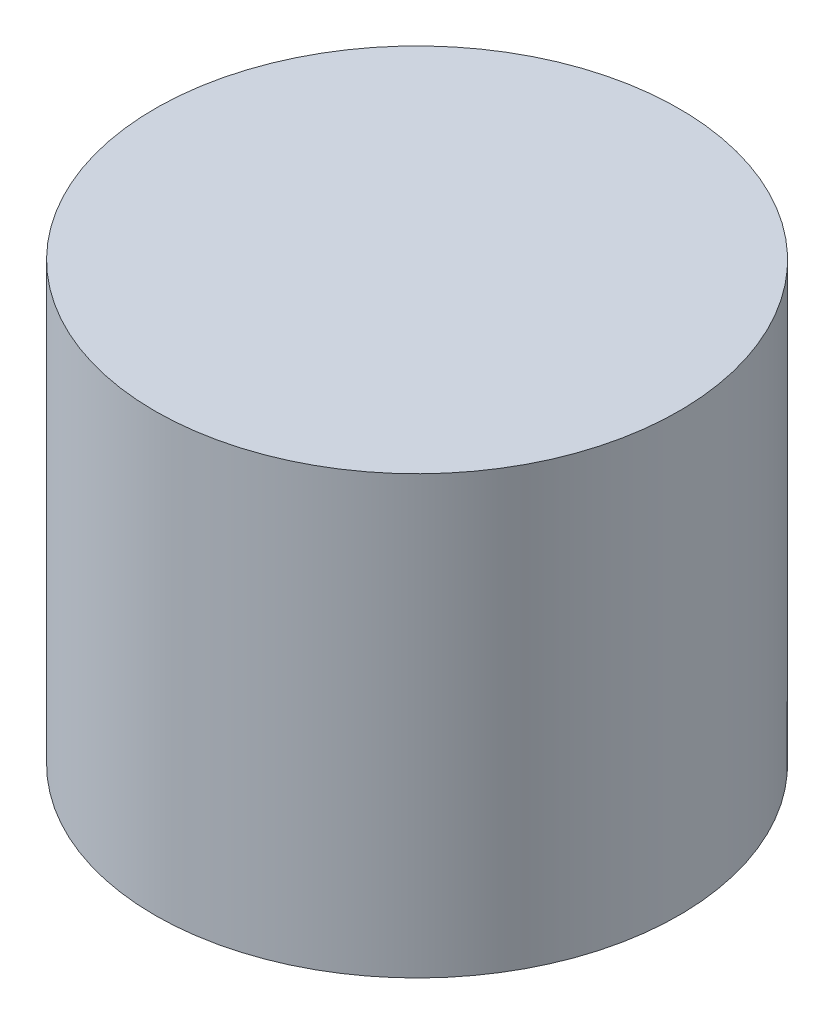
SolidWorks part; units mm, degrees
ref_plane "Front Plane" through (0, 0, 0) normal (0, 0, 1) x (1, 0, 0)
ref_plane "Top Plane" through (0, 0, 0) normal (0, 1, 0) x (1, 0, 0)
ref_plane "Right Plane" through (0, 0, 0) normal (1, 0, 0) x (0, 0, -1)
sketch "Sketch1" plane through (0, 0, 0) normal (0, 1, 0) x (1, 0, 0)
  circle A0 centre (0, 0) radius 6
  dimension "D1" = 12
extrude "Boss-Extrude1" add sketch "Sketch1" along normal blind 10
equation "\"dai_truc\"=10"
